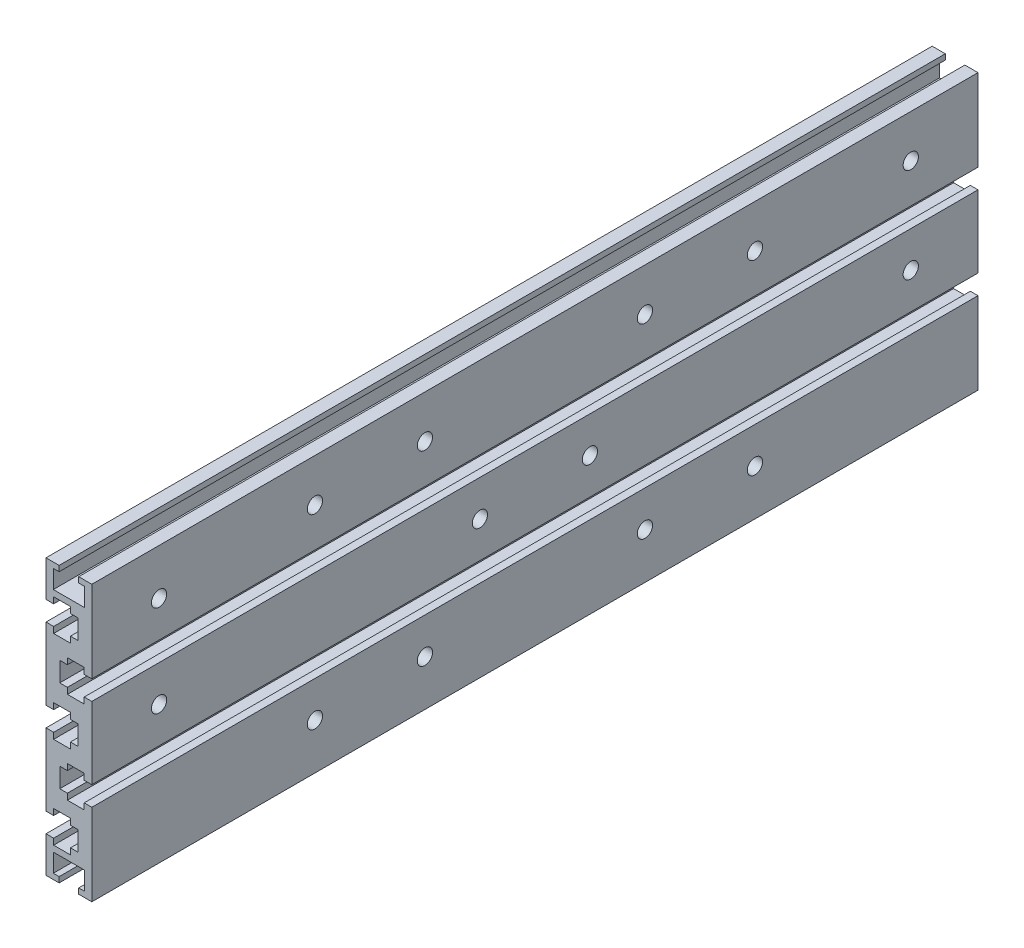
SolidWorks part; units mm, degrees
ref_plane "Plane1" through (0, 0, 0) normal (0, 0, 1) x (1, 0, 0)
ref_plane "Plane2" through (0, 0, 0) normal (0, 1, 0) x (1, 0, 0)
ref_plane "Plane3" through (0, 0, 0) normal (1, 0, 0) x (0, 0, -1)
sketch "Sketch1" plane through (0, 0, 0) normal (0, 0, 1) x (1, 0, 0)
  line L0 (0, 0) -> (75.649, 0) construction
  line L1 (-6.5, 45) -> (-3.2, 45)
  line L2 (-7.5, 44) -> (-7.5, 33.2)
  line L3 (-6.4967, -45) -> (-3.2, -45)
  line L4 (7.5, 44) -> (7.5, 18.2)
  line L5 (0, 3.6903) -> (0, 44.6054) construction
  line L6 (-3.2, 45) -> (-3.2, 43.2)
  line L7 (-3.2, 43.2) -> (-5.1, 43.2)
  line L8 (-5.1, 43.2) -> (-5.1, 37.2)
  line L9 (-5.1, 37.2) -> (5.1, 37.2)
  line L10 (5.1, 37.2) -> (5.1, 43.2)
  line L11 (5.1, 43.2) -> (3.2, 43.2)
  line L12 (3.2, 43.2) -> (3.2, 45)
  line L13 (3.2, 45) -> (6.5, 45)
  line L14 (3.2, -43.2) -> (3.2, -45)
  line L15 (5.1, -43.2) -> (3.2, -43.2)
  line L16 (5.1, -37.2) -> (5.1, -43.2)
  line L17 (-5.1, -37.2) -> (5.1, -37.2)
  line L18 (-5.1, -43.2) -> (-5.1, -37.2)
  line L19 (-3.2, -43.2) -> (-5.1, -43.2)
  line L20 (-3.2, -45) -> (-3.2, -43.2)
  line L21 (3.2, -45) -> (6.5, -45)
  line L22 (-5, -5.2) -> (0.5, -5.2)
  line L23 (-7.5, -3.2) -> (-5, -3.2)
  line L24 (-5, 3.2) -> (-7.5, 3.2)
  line L25 (0.5, -5.2) -> (0.5, -3.2)
  line L26 (-5, -3.2) -> (-5, -5.2)
  line L27 (0.5, 5.2) -> (-5, 5.2)
  line L28 (-17.4711, 15) -> (26.2798, 15) construction
  line L29 (-5, 5.2) -> (-5, 3.2)
  line L30 (-17.4711, -15) -> (26.2798, -15) construction
  line L31 (-3, -11.8) -> (-3, -18.2)
  line L32 (-0.5, -20.2) -> (-0.5, -18.2)
  line L33 (5, -11.8) -> (7.5, -11.8)
  line L34 (5, -18.2) -> (5, -20.2)
  line L35 (-0.5, -11.8) -> (-0.5, -9.8)
  line L36 (0.5, 3.2) -> (3, 3.2)
  line L37 (3, 3.2) -> (3, -3.2)
  line L38 (3, -3.2) -> (0.5, -3.2)
  line L39 (0.5, 3.2) -> (0.5, 5.2)
  line L40 (-7.5, -3.2) -> (-7.5, -26.8)
  line L41 (5, 9.8) -> (5, 11.8)
  line L42 (5, 20.2) -> (-0.5, 20.2)
  line L43 (-0.5, 9.8) -> (5, 9.8)
  line L44 (-3, 18.2) -> (-0.5, 18.2)
  line L45 (7.5, 18.2) -> (5, 18.2)
  line L46 (-0.5, 11.8) -> (-3, 11.8)
  line L47 (-0.5, 11.8) -> (-0.5, 9.8)
  line L48 (5, 18.2) -> (5, 20.2)
  line L49 (-0.5, -11.8) -> (-3, -11.8)
  line L50 (5, 11.8) -> (7.5, 11.8)
  line L51 (-0.5, 20.2) -> (-0.5, 18.2)
  line L52 (7.5, -18.2) -> (5, -18.2)
  line L53 (-3, 11.8) -> (-3, 18.2)
  line L54 (-3, -18.2) -> (-0.5, -18.2)
  line L55 (-0.5, -9.8) -> (5, -9.8)
  line L56 (5, -20.2) -> (-0.5, -20.2)
  line L57 (5, -9.8) -> (5, -11.8)
  line L58 (7.5, 11.8) -> (7.5, -11.8)
  line L59 (7.5, -18.2) -> (7.5, -44)
  line L60 (-6.5, 45) -> (-7.5, 45)
  line L61 (-7.5, 45) -> (-7.5, 44)
  line L62 (7.5, 44) -> (7.5, 45)
  line L63 (7.5, 45) -> (6.5, 45)
  line L64 (-7.5, -44) -> (-7.5, -45)
  line L65 (-7.5, -45) -> (-6.4967, -45)
  line L66 (6.5, -45) -> (7.5, -45)
  line L67 (7.5, -45) -> (7.5, -44)
  line L68 (-7.5, -26.8) -> (-5, -26.8)
  line L69 (-5, -33.2) -> (-7.5, -33.2)
  line L70 (0.5, -33.2) -> (0.5, -35.2)
  line L71 (3, -26.8) -> (0.5, -26.8)
  line L72 (3, -33.2) -> (3, -26.8)
  line L73 (0.5, -33.2) -> (3, -33.2)
  line L74 (-5, -35.2) -> (-5, -33.2)
  line L75 (0.5, -35.2) -> (-5, -35.2)
  line L76 (-5, -26.8) -> (-5, -24.8)
  line L77 (0.5, -24.8) -> (0.5, -26.8)
  line L78 (-5, -24.8) -> (0.5, -24.8)
  line L79 (-7.5, -33.2) -> (-7.5, -44)
  line L80 (-7.5, 33.2) -> (-5, 33.2)
  line L81 (-5, 26.8) -> (-7.5, 26.8)
  line L82 (0.5, 26.8) -> (0.5, 24.8)
  line L83 (3, 33.2) -> (0.5, 33.2)
  line L84 (3, 26.8) -> (3, 33.2)
  line L85 (0.5, 26.8) -> (3, 26.8)
  line L86 (-5, 24.8) -> (-5, 26.8)
  line L87 (0.5, 24.8) -> (-5, 24.8)
  line L88 (-5, 33.2) -> (-5, 35.2)
  line L89 (0.5, 35.2) -> (0.5, 33.2)
  line L90 (-5, 35.2) -> (0.5, 35.2)
  line L91 (-7.5, 26.8) -> (-7.5, 3.2)
  point P72 (-7.5, 45)
  point P73 (7.5, 45)
  point P74 (0, 45)
  point P75 (-7.5, -45)
  point P76 (7.5, -45)
  point P77 (0, -45)
  point P78 (7.5, -15)
  point P79 (-7.5, 0)
  point P80 (7.5, 15)
  point P81 (-7.5, 15)
  point P82 (7.5, 0)
  point P83 (-7.5, -15)
extrude "凸台-拉伸1" add sketch "Sketch1" along normal blind 290
ref_plane "基准面1" through (7.5, 45, 290) normal (-1, 0, 0) x (0, 0, 1)
ref_plane "基准面2" through (-7.5, 45, 290) normal (-1, 0, 0) x (0, 0, 1)
hole_wizard "Ø5.0 (5) 直径孔1" positions "草图2" profile "草图1" hole size "Ø5.0" standard "Gb" end condition through all
sketch "草图2" plane through (7.5, 0, 0) normal (1, 0, 0) x (0, 0, -1)
  line L0 (-290, 18.2) -> (-290, 45) construction
  line L2 (-290, 45) -> (0, 45) construction
  point P0 (-268, 30)
  point P8 (-271.8798, 45)
  point P15 (-301.4685, 14.6253)
  dimension "D1" = 22
  dimension "D2" = 15
sketch "草图1" plane through (7.5, 30, 268) normal (0, 1, 0) x (0, 0, -1)
  line L0 (0, 0) -> (0, 15)
  line L1 (0, 15) -> (2.5, 15)
  line L2 (2.5, 15) -> (2.5, 0)
  line L5 (2.5, 0) -> (0, 0)
  line L11 (0, -6.35) -> (0, 107.95) construction
  dimension "通孔孔直径" = 5
  dimension "通孔孔深度" = 15
hole_wizard "Ø5.0 (5) 直径孔2" positions "草图4" profile "草图3" hole size "Ø5.0" standard "Gb"
sketch "草图4" plane through (7.5, 0, 0) normal (1, 0, 0) x (0, 0, -1)
  line L0 (-290, -45) -> (0, -45) construction
  line L1 (-290, -45) -> (-290, -18.2) construction
  line L2 (0, -11.8) -> (0, 11.8) construction
  circle A0 centre (-268, 30) radius 2.5 construction
  point P0 (-217, 30.9861)
  point P2 (-181, 30.9861)
  point P4 (-109, 30.9861)
  point P6 (-73, 30.9861)
  point P8 (-22, 30.9861)
  point P10 (-268, 0)
  point P12 (-217, -30)
  point P14 (-181, -30)
  point P16 (-163, 0)
  point P18 (-127, 0)
  point P20 (-109, -30)
  point P22 (-73, -30)
  point P24 (-22, 0)
  dimension "D1" = 45
  dimension "D2" = 22
  dimension "D3" = 73
  dimension "D4" = 15
  dimension "D5" = 109
  dimension "D6" = 181
  dimension "D7" = 217
  dimension "D8" = 22
  dimension "D9" = 127
  dimension "D10" = 163
sketch "草图3" plane through (7.5, 30.9861, 217) normal (0, 1, 0) x (0, 0, -1)
  line L0 (0, 0) -> (0, 21.5022)
  line L1 (0, 21.5022) -> (2.5, 20)
  line L2 (2.5, 20) -> (2.5, 0)
  line L5 (2.5, 0) -> (0, 0)
  line L10 (0, 21.5022) -> (-2.5, 20) construction
  line L11 (0, -6.35) -> (0, 107.95) construction
  dimension "孔直径" = 5
  dimension "孔深度" = 20
  dimension "导头角度" = 118
